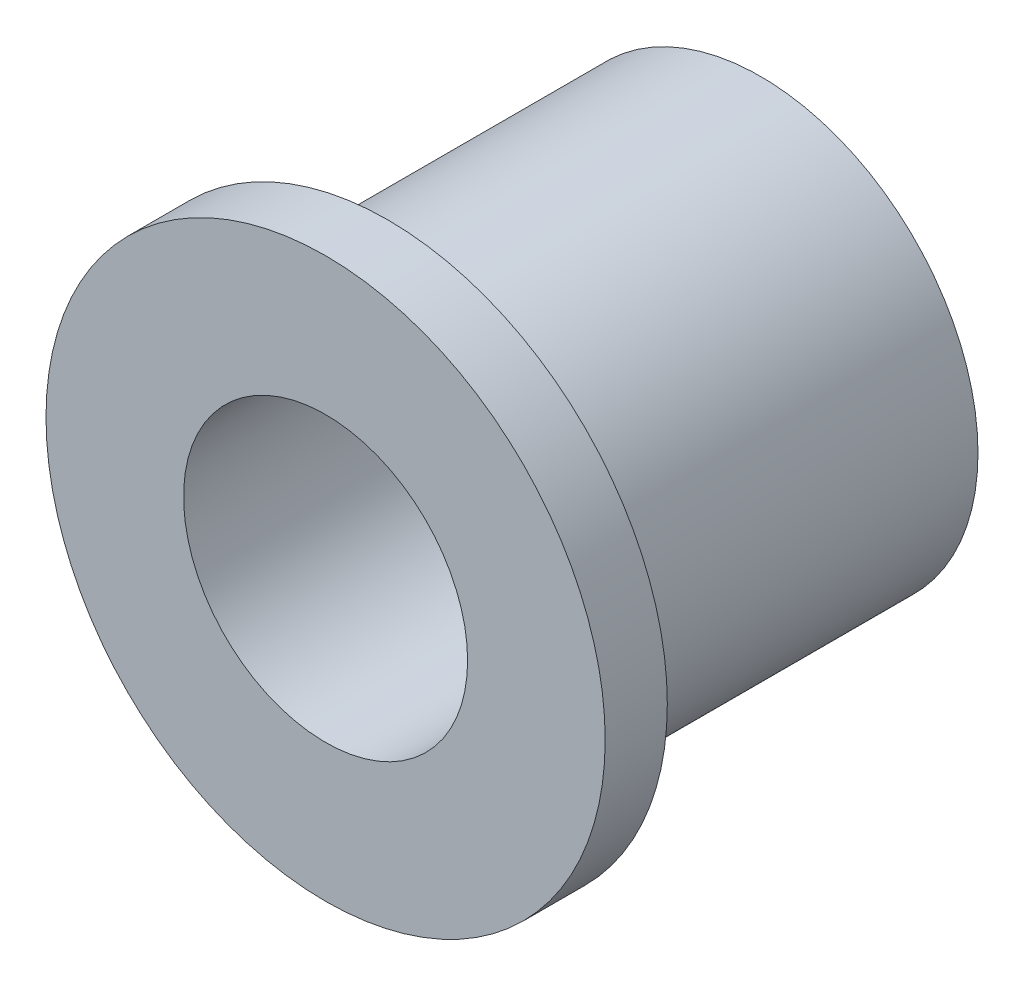
SolidWorks part; units mm, degrees
material "Brass"
ref_plane "Front Plane" through (0, 0, 0) normal (0, 0, 1) x (1, 0, 0)
ref_plane "Top Plane" through (0, 0, 0) normal (0, 1, 0) x (1, 0, 0)
ref_plane "Right Plane" through (0, 0, 0) normal (1, 0, 0) x (0, 0, -1)
sketch "Sketch1" plane through (0, 0, 0) normal (0, 1, 0) x (1, 0, 0)
  line L0 (-3.6286, 0) -> (-7.1437, 0)
  line L1 (-7.1437, 0) -> (-7.1437, 1.5875)
  line L2 (-7.1437, 1.5875) -> (-5.5562, 1.5875)
  line L3 (-5.5562, 1.5875) -> (-5.5562, 11.1125)
  line L4 (-5.5562, 11.1125) -> (-3.6286, 11.1125)
  line L5 (-3.6286, 11.1125) -> (-3.6286, 0)
  line L6 (0, 0) -> (0, 29.273) construction
  dimension "D1" = 3.6286
  dimension "D2" = 5.5562
  dimension "D3" = 9.525
  dimension "D4" = 1.5875
  dimension "D5" = 7.1437
revolve "Revolve1" add sketch "Sketch1" angle 360 about L6
equation "\"D1@Sketch1\"=5/35"
equation "\"D2@Sketch1\"=7/32"
equation "\"D3@Sketch1\"=3/8"
equation "\"D5@Sketch1\"=9/32"
